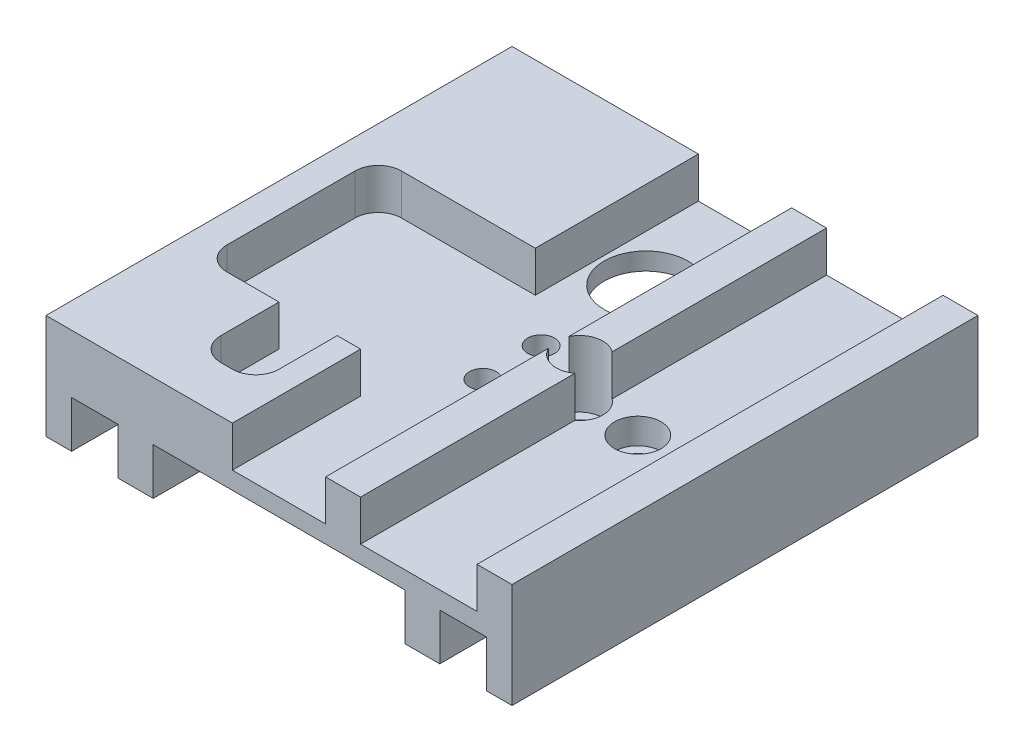
SolidWorks part; units mm, degrees
other "标注1"
sketch "草图13" plane through (0, 0, 40) normal (0, 0, 1) x (1, 0, 0)
ref_plane "前视基准面" through (0, 0, 0) normal (0, 0, 1) x (1, 0, 0)
ref_plane "上视基准面" through (0, 0, 0) normal (0, 1, 0) x (1, 0, 0)
ref_plane "右视基准面" through (0, 0, 0) normal (1, 0, 0) x (0, 0, -1)
other "Configuration Table"
sketch "草图1" plane through (0, 0, 0) normal (0, 1, 0) x (1, 0, 0)
  line L1 (0, 0) -> (40, 0)
  line L2 (0, 0) -> (0, -40)
  line L3 (0, -40) -> (40, -40)
  line L4 (40, 0) -> (40, -40)
  dimension "D1" = 40
  dimension "D2" = 40
extrude "凸台-拉伸1" add sketch "草图1" along normal blind 9
sketch "草图2" plane through (0, 9, 0) normal (0, 1, 0) x (1, 0, 0)
  line L0 (40, 0) -> (0, 0) construction
  line L1 (16, 0) -> (24, 0)
  line L2 (16, 0) -> (16, -40)
  line L3 (16, -40) -> (24, -40)
  line L4 (24, 0) -> (24, -40)
  line L5 (0, -40) -> (40, -40) construction
  line L6 (0, -20) -> (16, -20) construction
  line L7 (0, 0) -> (0, -40) construction
  line L8 (24, -20) -> (40, -20) construction
  line L9 (40, -40) -> (40, 0) construction
  dimension "D1" = 8
  dimension "D2" = 16
extrude "切除-拉伸1" cut sketch "草图2" against normal blind 3.5
sketch "草图3" plane through (0, 0, 0) normal (0, -1, 0) x (-1, 0, 0)
  line L0 (-16, -39) -> (-24, -39) construction
  line L1 (-16, 0) -> (-16, -40) construction
  line L2 (-24, -40) -> (-24, 0) construction
  line L3 (-20, -39) -> (-20, -22.5) construction
  line L4 (-20, -22.5) -> (-20, -17.5) construction
  line L5 (-16, -1) -> (-24, -1) construction
  line L6 (0, -40) -> (-40, -40) construction
  line L7 (-40, 0) -> (0, 0) construction
  line L8 (-20, -17.5) -> (-20, -1) construction
  circle A0 centre (-20, -22.5) radius 1.15
  circle A1 centre (-20, -17.5) radius 1.15
  dimension "D4" = 2.3
  dimension "D1" = 5
  dimension "D2" = 1
  dimension "D3" = 1
extrude "切除-拉伸2" cut sketch "草图3" against normal through all
sketch "草图4" plane through (0, 0, 0) normal (0, -1, 0) x (-1, 0, 0)
  circle A0 centre (-20, -22.5) radius 2
  circle A1 centre (-20, -17.5) radius 2
  dimension "D1" = 4
extrude "切除-拉伸3" cut sketch "草图4" against normal blind 2.4
sketch "草图5" plane through (0, 9, 0) normal (0, 1, 0) x (1, 0, 0)
  line L0 (0, -20) -> (25.8, -20) construction
  line L1 (0, 0) -> (0, -40) construction
  line L2 (25.8, -20) -> (30.8, -20) construction
  line L3 (30.8, -20) -> (40, -20) construction
  line L4 (40, -40) -> (40, 0) construction
  circle A0 centre (25.8, -20) radius 1.2
  circle A1 centre (30.8, -20) radius 1.2
  dimension "D2" = 2.4
  dimension "D3" = 9.2
  dimension "D1" = 5
extrude "切除-拉伸4" cut sketch "草图5" against normal through all
sketch "草图6" plane through (0, 9, 0) normal (0, 1, 0) x (1, 0, 0)
  circle A0 centre (30.8, -20) radius 2
  circle A1 centre (25.8, -20) radius 2
  dimension "D1" = 4
extrude "切除-拉伸5" cut sketch "草图6" against normal blind 5.7
sketch "草图7" plane through (0, 9, 0) normal (0, 1, 0) x (1, 0, 0)
  line L1 (2.5209, -14) -> (16, -14)
  line L2 (2.5209, -14) -> (2.5209, -29)
  line L3 (2.5209, -29) -> (16, -29)
  line L4 (16, -14) -> (16, -29)
  line L5 (20, -17.5) -> (20, -22.5) construction
  line L6 (20, -20) -> (50020, -20) construction
  point P12 (20, -20)
  dimension "D1" = 6
  dimension "D2" = 9
extrude "切除-拉伸6" cut sketch "草图7" against normal blind 3.5
sketch "草图12" plane through (0, 0, 0) normal (0, -1, 0) x (-1, 0, 0)
  line L0 (0, -40) -> (-40, -40) construction
  line L1 (-2.2, -40) -> (-6.2, -40)
  line L2 (-2.2, -40) -> (-2.2, 0)
  line L3 (-2.2, 0) -> (-6.2, 0)
  line L4 (-6.2, -40) -> (-6.2, 0)
  line L5 (-40, 0) -> (0, 0) construction
  line L6 (0, 0) -> (0, -40) construction
  line L7 (-33.8, -40) -> (-37.8, -40)
  line L8 (-33.8, -40) -> (-33.8, 0)
  line L9 (-33.8, 0) -> (-37.8, 0)
  line L10 (-37.8, -40) -> (-37.8, 0)
  line L12 (-40, -40) -> (-40, 0) construction
  line L14 (-30.8, 0) -> (-9.2, 0)
  line L15 (-30.8, 0) -> (-30.8, -12)
  line L16 (-30.8, -12) -> (-9.2, -12)
  line L17 (-9.2, 0) -> (-9.2, -12)
  line L18 (-9.2, -40) -> (-30.8, -40)
  line L19 (-9.2, -40) -> (-9.2, -26)
  line L20 (-9.2, -26) -> (-30.8, -26)
  line L21 (-30.8, -40) -> (-30.8, -26)
  dimension "D1" = 4
  dimension "D2" = 4
  dimension "D3" = 2.2
  dimension "D4" = 2.2
  dimension "D5" = 21.6
  dimension "D6" = 21.6
  dimension "D7" = 3
  dimension "D8" = 3
  dimension "D9" = 14
  dimension "D10" = 12
extrude "切除-拉伸11" cut sketch "草图12" against normal blind 4
fillet "圆角3" radius 2 4 edges at (30.8, 2, 12) (9.2, 2, 12) (30.8, 2, 26) (9.2, 2, 26)
sketch "草图15" plane through (0, 5.5, 0) normal (0, 1, 0) x (1, 0, 0)
  line L0 (20, -8.5) -> (20, -40) construction
  line L1 (16, -40) -> (24, -40) construction
  line L2 (40, 0) -> (24, 0) construction
  circle A0 centre (20, -8.5) radius 3.6
  dimension "D1" = 7.2
  dimension "D2" = 8.5
extrude "切除-拉伸13" cut sketch "草图15" against normal blind 4
sketch "草图16" plane through (0, 9, 0) normal (0, 1, 0) x (1, 0, 0)
  line L0 (2.5209, -29) -> (16, -29) construction
  line L1 (9, -29) -> (14, -29)
  line L2 (9, -29) -> (9, -36)
  line L3 (9, -36) -> (14, -36)
  line L4 (14, -29) -> (14, -36)
  line L5 (16, -29) -> (16, -40) construction
  dimension "D1" = 5
  dimension "D2" = 7
  dimension "D3" = 2
extrude "切除-拉伸14" cut sketch "草图16" against normal blind 3.5
sketch "草图17" plane through (0, 5.5, 0) normal (0, 1, 0) x (1, 0, 0)
  line L0 (9, -36) -> (14, -36) construction
  line L1 (11.5, -34) -> (11.5, -36) construction
  circle A0 centre (11.5, -34) radius 1.5
  dimension "D1" = 3
  dimension "D2" = 2
extrude "切除-拉伸15" cut sketch "草图17" against normal blind 3.5
fillet "圆角5" radius 2 4 edges at (14, 7.25, 36) (9, 7.25, 36) (2.5209, 7.25, 29) (2.5209, 7.25, 14)
sketch "草图18" plane through (0, 9, 0) normal (0, 1, 0) x (1, 0, 0)
  line L0 (40, 0) -> (24, 0) construction
  line L1 (27, 0) -> (37, 0)
  line L2 (27, 0) -> (27, -40)
  line L3 (27, -40) -> (37, -40)
  line L4 (37, 0) -> (37, -40)
  line L5 (24, -40) -> (40, -40) construction
  line L6 (40, -40) -> (40, 0) construction
  dimension "D1" = 10
  dimension "D2" = 3
extrude "切除-拉伸16" cut sketch "草图18" against normal blind 3.5
